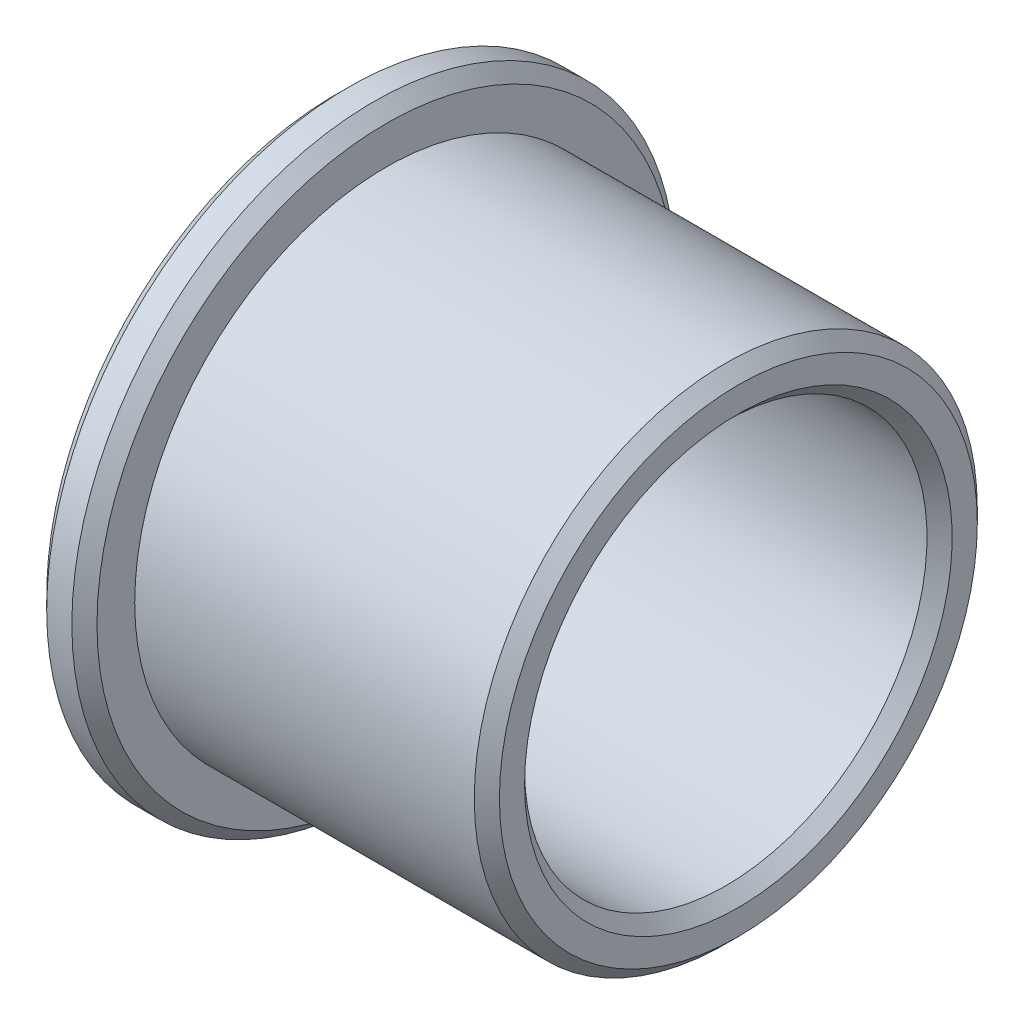
SolidWorks part; units mm, degrees
ref_plane "Plan de face" through (0, 0, 0) normal (0, 0, 1) x (1, 0, 0)
ref_plane "Plan de dessus" through (0, 0, 0) normal (0, 1, 0) x (1, 0, 0)
ref_plane "Plan de droite" through (0, 0, 0) normal (1, 0, 0) x (0, 0, -1)
sketch "Esquisse1" plane through (0, 0, 0) normal (0, 1, 0) x (1, 0, 0)
  line L0 (-2.3158, 0) -> (7.9474, 0) construction
  line L1 (8, 5) -> (1, 5)
  line L2 (1, 5) -> (1, 6)
  line L3 (1, 6) -> (0, 6)
  line L4 (0, 6) -> (0, 4)
  line L5 (0, 4) -> (8, 4)
  line L6 (8, 4) -> (8, 5)
  dimension "D1" = 1
  dimension "D2" = 1
  dimension "D3" = 7
  dimension "D4" = 1
  dimension "D5" = 4
revolve "Révolution1" add sketch "Esquisse1" angle 360 about L0
chamfer "Chanfrein1" distance 0.25 angle 45 5 edges at (0, 0, 6) (1, 0, 6) (0, 0, 4) (8, 0, 4) (8, 0, 5)
